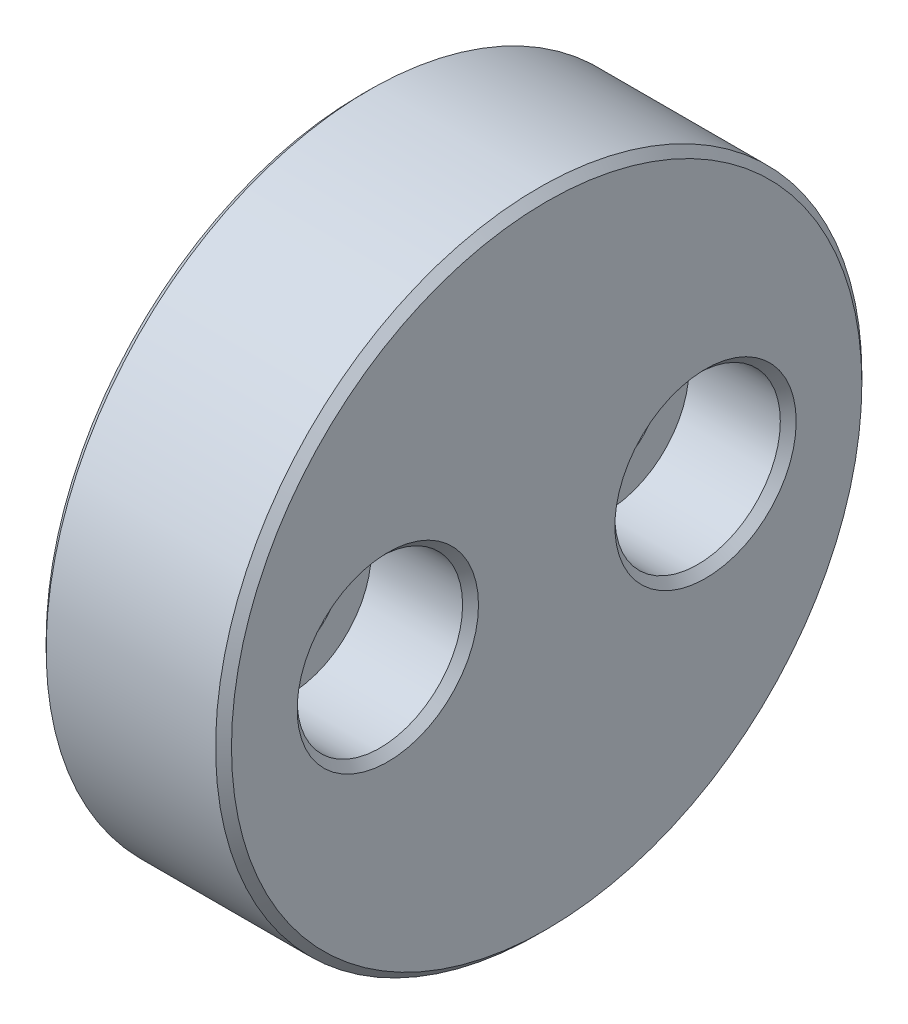
SolidWorks part; units mm, degrees
material "Plain Carbon Steel"
ref_plane "Front Plane" through (0, 0, 0) normal (0, 0, 1) x (1, 0, 0)
ref_plane "Top Plane" through (0, 0, 0) normal (0, 1, 0) x (1, 0, 0)
ref_plane "Right Plane" through (0, 0, 0) normal (1, 0, 0) x (0, 0, -1)
sketch "Sketch1" plane through (0, 0, 0) normal (1, 0, 0) x (0, 0, -1)
  circle A1 centre (0, 0) radius 31
  dimension "D1" = 62
extrude "Boss-Extrude1" add sketch "Sketch1" along normal blind 17.78
hole_wizard "CBORE for 3/8 Socket Head Cap Screw1" positions "Sketch3" profile "Sketch2" counterbore size "3/8" standard "ANSI Inch"
sketch "Sketch3" plane through (17.78, 0, 0) normal (1, 0, 0) x (0, 0, -1)
  line L0 (-15.24, 0) -> (15.24, 0) construction
  point P0 (-15.24, 0)
  point P2 (15.24, 0)
  point P11 (-15.24, 0)
  dimension "D1" = 30.48
sketch "Sketch2" plane through (17.78, 0, 15.24) normal (0, 1, 0) x (0, 0, -1)
  line L0 (0, 0) -> (0, 26.7707)
  line L1 (0, 26.7707) -> (4.9022, 23.8252)
  line L2 (4.9022, 23.8252) -> (4.9022, 9.525)
  line L3 (4.9022, 9.525) -> (7.9375, 9.525)
  line L4 (7.9375, 9.525) -> (7.9375, 0)
  line L5 (7.9375, 0) -> (0, 0)
  line L10 (0, 26.7707) -> (-4.9022, 23.8252) construction
  line L11 (0, -6.35) -> (0, 107.95) construction
  dimension "Hole Dia." = 9.8044
  dimension "Hole Depth" = 23.8252
  dimension "C'Bore Dia." = 15.875
  dimension "C'Bore Depth" = 9.525
  dimension "Drill Angle" = 118
chamfer "Chamfer1" distance 0.762 angle 45 4 edges at (0, 0, -31) (17.78, 0, -23.1775) (17.78, 0, 7.3025) (17.78, 0, -31)
